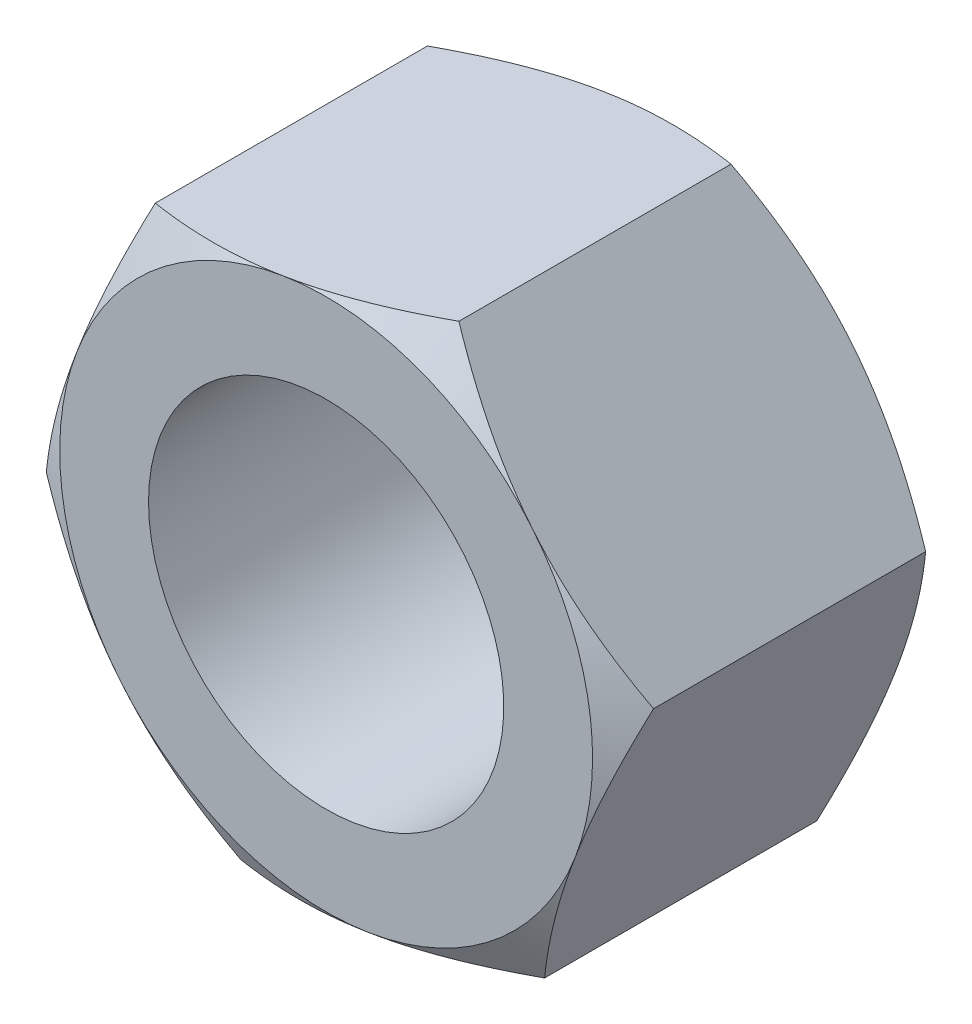
SolidWorks part; units mm, degrees
ref_plane "Front Plane" through (0, 0, 0) normal (0, 0, 1) x (1, 0, 0)
ref_plane "Top Plane" through (0, 0, 0) normal (0, 1, 0) x (1, 0, 0)
ref_plane "Right Plane" through (0, 0, 0) normal (1, 0, 0) x (0, 0, -1)
sketch "Sketch1" plane through (0, 0, 0) normal (0, 0, 1) x (1, 0, 0)
  line L1 (6.1341, 16.1979) -> (-10.9607, 13.4113)
  line L2 (-10.9607, 13.4113) -> (-17.0949, -2.7867)
  line L3 (-17.0949, -2.7867) -> (-6.1341, -16.1979)
  line L4 (-6.1341, -16.1979) -> (10.9607, -13.4113)
  line L5 (10.9607, -13.4113) -> (17.0949, 2.7867)
  line L6 (17.0949, 2.7867) -> (6.1341, 16.1979)
  circle A0 centre (0, 0) radius 15 construction
  dimension "D1" = 30
extrude "Boss-Extrude1" add sketch "Sketch1" along normal blind 18
sketch "Sketch2" plane through (0, 0, 18) normal (0, 0, 1) x (1, 0, 0)
  circle A0 centre (0, 0) radius 15
extrude "Cut-Extrude1" cut sketch "Sketch2" against normal blind 18 draft 60 flip side to cut
sketch "Sketch3" plane through (0, 0, 0) normal (0, 0, -1) x (-1, 0, 0)
  circle A0 centre (0, 0) radius 15
extrude "Cut-Extrude2" cut sketch "Sketch3" against normal blind 18 draft 60 flip side to cut
sketch "Sketch4" plane through (0, 0, 0) normal (0, 0, -1) x (-1, 0, 0)
  circle A0 centre (0, 0) radius 10
  dimension "D1" = 20
extrude "Cut-Extrude3" cut sketch "Sketch4" against normal through all
